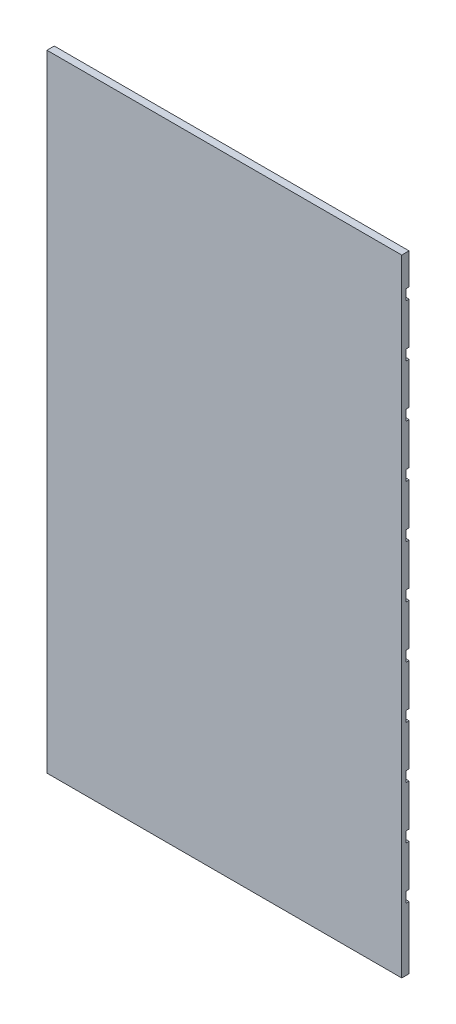
SolidWorks part; units mm, degrees
ref_plane "Front Plane" through (0, 0, 0) normal (0, 0, 1) x (1, 0, 0)
ref_plane "Top Plane" through (0, 0, 0) normal (0, 1, 0) x (1, 0, 0)
ref_plane "Right Plane" through (0, 0, 0) normal (1, 0, 0) x (0, 0, -1)
sketch "Sketch2" plane through (0, 0, 0) normal (1, 0, 0) x (0, 0, -1)
  line L1 (0, 0) -> (17.78, 0)
  line L2 (0, 0) -> (0, -1524)
  line L3 (0, -1524) -> (17.78, -1524)
  line L4 (17.78, 0) -> (17.78, -1524)
  dimension "D1" = 17.78
  dimension "D2" = 1524
extrude "Boss-Extrude1" add sketch "Sketch2" along normal blind 863.6
sketch "Sketch3" plane through (0, 0, -17.78) normal (0, 0, -1) x (-1, 0, 0)
  line L0 (-863.6, -1524) -> (-863.6, 0) construction
  line L1 (-863.6, -76.2) -> (0, -76.2)
  line L2 (-863.6, -76.2) -> (-863.6, -101.6)
  line L3 (-863.6, -101.6) -> (0, -101.6)
  line L4 (0, -76.2) -> (0, -101.6)
  line L5 (0, -1524) -> (0, 0) construction
  line L6 (-863.6, 0) -> (0, 0) construction
  line L7 (-863.6, -228.6) -> (0, -228.6)
  line L8 (-863.6, -203.2) -> (0, -203.2)
  line L9 (-863.6, -203.2) -> (-863.6, -228.6)
  line L10 (0, -203.2) -> (0, -228.6)
  line L11 (-863.6, -355.6) -> (0, -355.6)
  line L12 (-863.6, -330.2) -> (0, -330.2)
  line L13 (-863.6, -330.2) -> (-863.6, -355.6)
  line L14 (0, -330.2) -> (0, -355.6)
  line L15 (-863.6, -482.6) -> (0, -482.6)
  line L16 (-863.6, -457.2) -> (0, -457.2)
  line L17 (-863.6, -457.2) -> (-863.6, -482.6)
  line L18 (0, -457.2) -> (0, -482.6)
  line L19 (-863.6, -609.6) -> (0, -609.6)
  line L20 (-863.6, -584.2) -> (0, -584.2)
  line L21 (-863.6, -584.2) -> (-863.6, -609.6)
  line L22 (0, -584.2) -> (0, -609.6)
  line L23 (-863.6, -736.6) -> (0, -736.6)
  line L24 (-863.6, -711.2) -> (0, -711.2)
  line L25 (-863.6, -711.2) -> (-863.6, -736.6)
  line L26 (0, -711.2) -> (0, -736.6)
  line L27 (-863.6, -863.6) -> (0, -863.6)
  line L28 (-863.6, -838.2) -> (0, -838.2)
  line L29 (-863.6, -838.2) -> (-863.6, -863.6)
  line L30 (0, -838.2) -> (0, -863.6)
  line L31 (-863.6, -990.6) -> (0, -990.6)
  line L32 (-863.6, -965.2) -> (0, -965.2)
  line L33 (-863.6, -965.2) -> (-863.6, -990.6)
  line L34 (0, -965.2) -> (0, -990.6)
  line L35 (-863.6, -1117.6) -> (0, -1117.6)
  line L36 (-863.6, -1092.2) -> (0, -1092.2)
  line L37 (-863.6, -1092.2) -> (-863.6, -1117.6)
  line L38 (0, -1092.2) -> (0, -1117.6)
  line L39 (-863.6, -1244.6) -> (0, -1244.6)
  line L40 (-863.6, -1219.2) -> (0, -1219.2)
  line L41 (-863.6, -1219.2) -> (-863.6, -1244.6)
  line L42 (0, -1219.2) -> (0, -1244.6)
  line L43 (-863.6, -1371.6) -> (0, -1371.6)
  line L44 (-863.6, -1346.2) -> (0, -1346.2)
  line L45 (-863.6, -1346.2) -> (-863.6, -1371.6)
  line L46 (0, -1346.2) -> (0, -1371.6)
  dimension "D1" = 25.4
  dimension "D2" = 76.2
  dimension "D3" = 11
extrude "Cut-Extrude1" cut sketch "Sketch3" against normal blind 7.62
